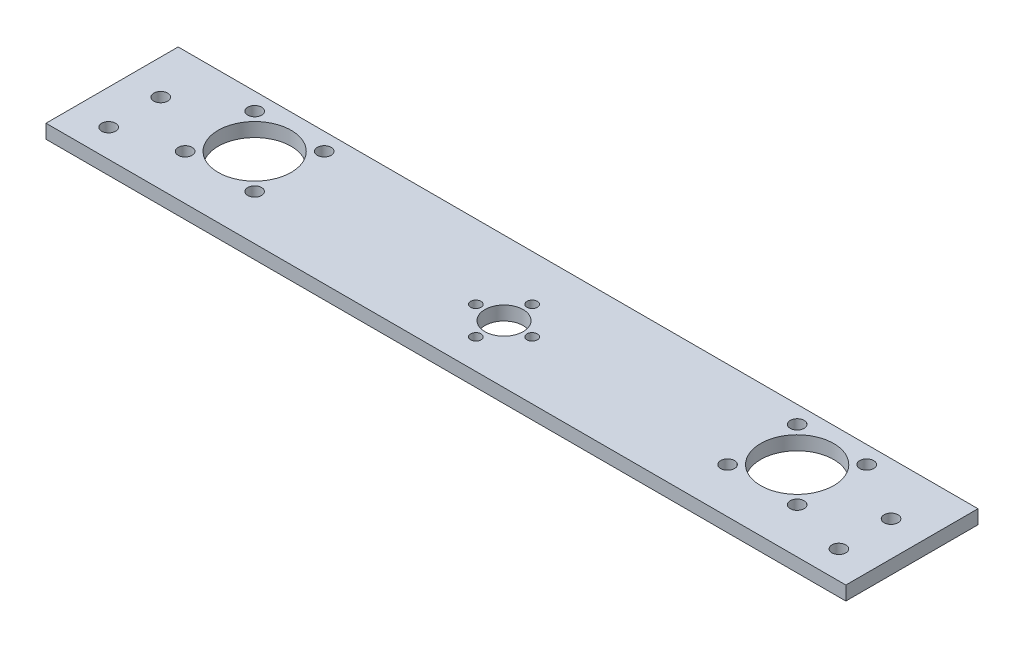
SolidWorks part; units mm, degrees
ref_plane "Front Plane" through (0, 0, 0) normal (0, 0, 1) x (1, 0, 0)
ref_plane "Top Plane" through (0, 0, 0) normal (0, 1, 0) x (1, 0, 0)
ref_plane "Right Plane" through (0, 0, 0) normal (1, 0, 0) x (0, 0, -1)
sketch "Sketch1" plane through (0, 0, 0) normal (0, 1, 0) x (1, 0, 0)
  line L0 (-112.5, -8) -> (112.5, -8)
  line L1 (-112.5, 30) -> (112.5, 30)
  line L2 (-112.5, 30) -> (-112.5, -8)
  line L3 (-112.5, -30) -> (112.5, -30) construction
  line L4 (112.5, 30) -> (112.5, -8)
  line L5 (-112.5, 30) -> (112.5, -30) construction
  line L6 (-112.5, -30) -> (112.5, 30) construction
  line L8 (-112.5, 30) -> (-112.5, -8) construction
  line L12 (112.5, 30) -> (112.5, -8) construction
  line L14 (-112.5, -30) -> (-112.5, -8) construction
  line L15 (112.5, -30) -> (112.5, -8) construction
  point P0 (0, 0)
  dimension "D1" = 60
  dimension "D2" = 225
  dimension "D3" = 38
extrude "Boss-Extrude1" add sketch "Sketch1" along normal blind 4
sketch "Sketch2" plane through (0, 4, 0) normal (0, 1, 0) x (1, 0, 0)
  line L0 (0, 30) -> (0, 3.2002) construction
  line L1 (112.5, 30) -> (-112.5, 30) construction
  line L3 (-80.5, 15) -> (75.5, 15) construction
  line L5 (112.5, -8) -> (112.5, 30) construction
  line L6 (-112.5, 30) -> (-112.5, -8) construction
  circle A0 centre (75.5, 15) radius 10.5
  circle A1 centre (-80.5, 15) radius 10.5
  circle A3 centre (-2.5, 8.7) radius 5.5
  dimension "D1" = 21
  dimension "D4" = 11
  dimension "D5" = 6.3
  dimension "D6" = 115
  dimension "D3" = 37
  dimension "D7" = 32
  dimension "D2" = 15
extrude "Cut-Extrude1" cut sketch "Sketch2" against normal up to next
sketch "Sketch10" plane through (0, 4, 0) normal (0, 1, 0) x (1, 0, 0)
  line L0 (-112.5, 30) -> (-112.5, -8) construction
  line L1 (-112.5, 30) -> (-117.5, 30)
  line L2 (-112.5, 30) -> (-112.5, -8)
  line L4 (-117.5, 30) -> (-117.5, -8)
  line L5 (112.5, 30) -> (-112.5, 30) construction
  line L9 (102.5, 30) -> (102.5, -8)
  line L10 (97.5, 30) -> (102.5, 30)
  line L11 (97.5, 30) -> (97.5, -8)
  line L12 (-112.5, -8) -> (-117.5, -8)
  line L13 (97.5, -8) -> (102.5, -8)
  line L14 (-112.5, -8) -> (112.5, -8) construction
  dimension "D1" = 5
  dimension "D2" = 38
  dimension "D3" = 38
  dimension "D4" = 210
  dimension "D5" = 5
extrude "Boss-Extrude2" add sketch "Sketch10" against normal blind 4
sketch "Sketch11" plane through (0, 4, 0) normal (0, 1, 0) x (1, 0, 0)
  line L0 (102.5, 0) -> (102.5, 15) construction
  line L2 (-2.5, -8) -> (-2.5, 30) construction
  line L3 (112.5, 30) -> (-117.5, 30) construction
  line L4 (-117.5, -8) -> (112.5, -8) construction
  line L5 (112.5, -8) -> (112.5, 30) construction
  circle A0 centre (102.5, 0) radius 2
  circle A1 centre (102.5, 15) radius 2
  circle A4 centre (-107.5, 15) radius 2
  circle A5 centre (-107.5, 0) radius 2
  dimension "D1" = 4
  dimension "D3" = 8
  dimension "D4" = 4
  dimension "D2" = 10
  dimension "D5" = 15
extrude "Cut-Extrude2" cut sketch "Sketch11" against normal blind 27
sketch "Sketch12" plane through (0, 4, 0) normal (0, 1, 0) x (1, 0, 0)
  line L1 (112.5, -8) -> (112.5, 30) construction
  line L2 (112.5, 30) -> (-117.5, 30) construction
  line L3 (-2.5, -8) -> (-2.5, 30) construction
  line L4 (-117.5, -8) -> (112.5, -8) construction
  circle A0 centre (65.5, 5) radius 2
  circle A1 centre (85.5, 5) radius 2
  circle A2 centre (85.5, 25) radius 2
  circle A3 centre (65.5, 25) radius 2
  circle A8 centre (-70.5, 25) radius 2
  circle A9 centre (-90.5, 25) radius 2
  circle A10 centre (-90.5, 5) radius 2
  circle A11 centre (-70.5, 5) radius 2
  dimension "D1" = 4
  dimension "D3" = 13
  dimension "D5" = 5
  dimension "D7" = 20
  dimension "D4" = 27
  dimension "D6" = 20
  dimension "D8" = 5
  dimension "D9" = 20
  dimension "D10" = 27
extrude "Cut-Extrude3" cut sketch "Sketch12" against normal blind 27
sketch "Sketch13" plane through (0, 4, 0) normal (0, 1, 0) x (1, 0, 0)
  line L0 (-2.5, 30) -> (-2.5, -8) construction
  line L1 (112.5, 30) -> (-117.5, 30) construction
  line L2 (-117.5, -8) -> (112.5, -8) construction
  circle A0 centre (-2.5, 16.7534) radius 1.7
sketch "Sketch14" plane through (0, 4, 0) normal (0, 1, 0) x (1, 0, 0)
  line L0 (-2.5, 8.7) -> (-2.5, -8) construction
  line L5 (-117.5, -8) -> (112.5, -8) construction
  line L6 (-117.5, 30) -> (-117.5, -8) construction
  line L7 (-2.5, 8.7) -> (-2.5, 30) construction
  line L8 (112.5, 30) -> (-117.5, 30) construction
  circle A4 centre (-2.5, 8.7) radius 5.5 construction
  circle A5 centre (-2.5, 16.8) radius 1.5
  dimension "D1" = 115
  dimension "D2" = 8.1
  dimension "D3" = 3
  dimension "D4" = 13.2
  dimension "D5" = 11
extrude "Cut-Extrude4" cut sketch "Sketch14" against normal blind 10
pattern_circular "CirPattern1" count 4 over 360 about axis through (-2.5, 0, -8.7) along (0, 1, 0) of "Cut-Extrude4"
